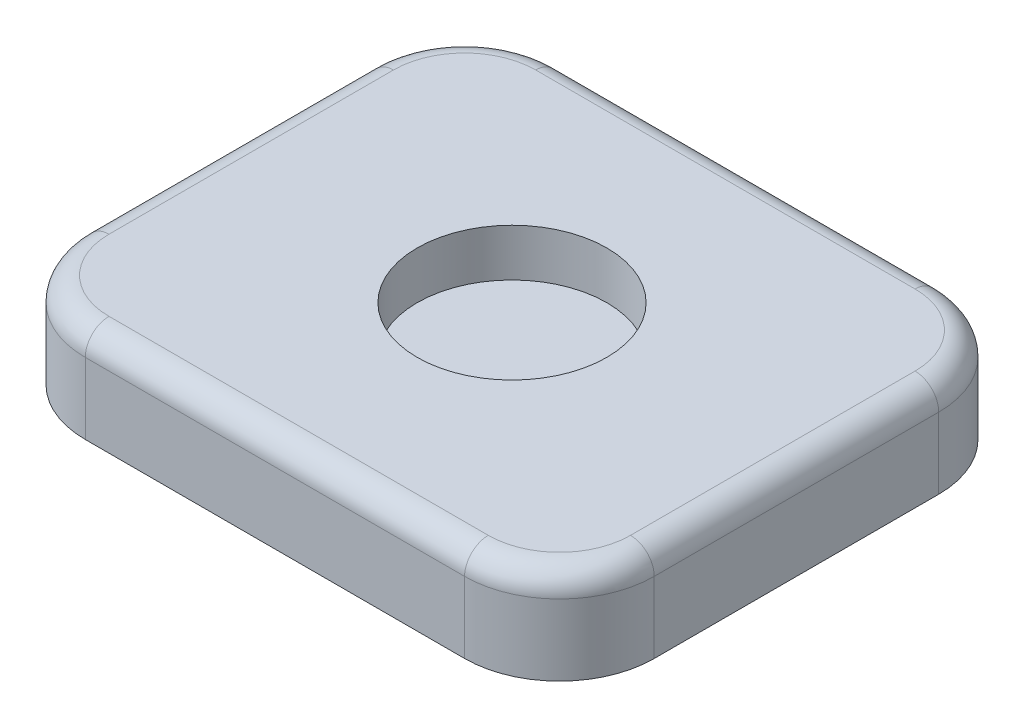
SolidWorks part; units mm, degrees
ref_plane "Front Plane" through (0, 0, 0) normal (0, 0, 1) x (1, 0, 0)
ref_plane "Top Plane" through (0, 0, 0) normal (0, 1, 0) x (1, 0, 0)
ref_plane "Right Plane" through (0, 0, 0) normal (1, 0, 0) x (0, 0, -1)
sketch "Sketch2" plane through (0, 0, 0) normal (0, 1, 0) x (1, 0, 0)
  line L1 (-60, 50) -> (60, 50)
  line L2 (-60, 50) -> (-60, -50)
  line L3 (-60, -50) -> (60, -50)
  line L4 (60, 50) -> (60, -50)
  line L5 (-60, 50) -> (60, -50) construction
  line L6 (-60, -50) -> (60, 50) construction
  circle A0 centre (0, 0) radius 20
  dimension "D1" = 120
  dimension "D3" = 40
  dimension "D2" = 100
extrude "Boss-Extrude1" add sketch "Sketch2" along normal blind 10
sketch "Sketch3" plane through (0, 0, 0) normal (0, -1, 0) x (1, 0, 0)
  line L1 (-60, 50) -> (60, 50)
  line L2 (-60, 50) -> (-60, -50)
  line L3 (-60, -50) -> (60, -50)
  line L4 (60, 50) -> (60, -50)
extrude "Boss-Extrude2" add sketch "Sketch3" along normal blind 10
fillet "Fillet1" radius 20 4 edges at (-60, 0, -50) (-60, 0, 50) (60, 0, -50) (60, 0, 50)
fillet "Fillet2" radius 5 8 edges at (60, 10, 0) (54.1421, 10, -44.1421) (0, 10, -50) (54.1421, 10, 44.1421) (0, 10, 50) (-54.1421, 10, 44.1421) (-60, 10, 0) (-54.1421, 10, -44.1421)
